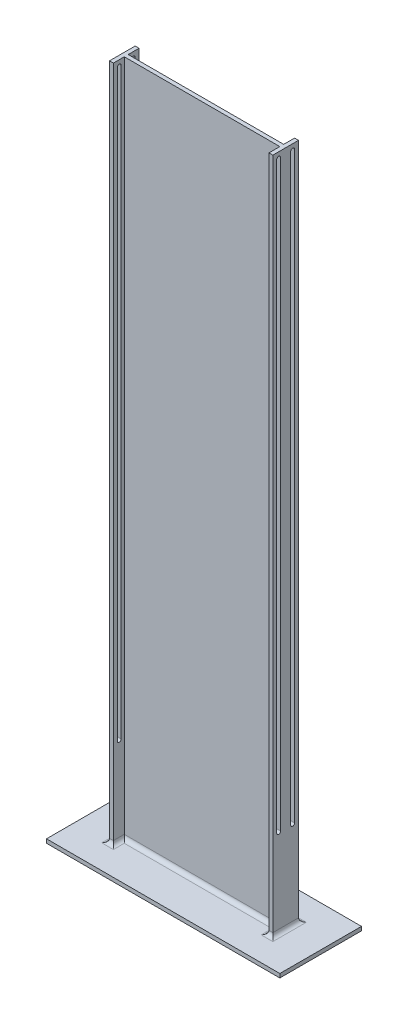
SolidWorks part; units mm, degrees
material "AISI 4340 Steel, annealed"
ref_plane "Front Plane" through (0, 0, 0) normal (0, 0, 1) x (1, 0, 0)
ref_plane "Top Plane" through (0, 0, 0) normal (0, 1, 0) x (1, 0, 0)
ref_plane "Right Plane" through (0, 0, 0) normal (1, 0, 0) x (0, 0, -1)
sketch "Sketch1" plane through (0, 0, 0) normal (1, 0, 0) x (0, 0, -1)
  line L0 (0, 0) -> (-100, 0)
  line L1 (-100, 0) -> (-100, -10)
  line L2 (-100, -10) -> (10, -10)
  line L3 (10, 0) -> (10, 1741.5)
  line L4 (10, 1741.5) -> (0, 1741.5)
  line L5 (0, 1741.5) -> (0, 0)
  line L6 (10, -10) -> (110, -10)
  line L7 (110, -10) -> (110, 0)
  line L8 (110, 0) -> (10, 0)
  point P3 (0, 0)
  dimension "D1" = 1751.5
  dimension "D2" = 10
  dimension "D3" = 10
  dimension "D4" = 100
extrude "Wall extrude" add sketch "Sketch1" along normal mid plane 400
sketch "Sketch2" plane through (200, 0, 0) normal (1, 0, 0) x (0, 0, -1)
  line L0 (5, 1741.5) -> (5, -10) construction
  line L1 (10, 1741.5) -> (0, 1741.5) construction
  line L2 (10, 0) -> (10, 1741.5) construction
  line L3 (-100, -10) -> (110, -10) construction
  line L4 (0, 1741.5) -> (38, 1741.5)
  line L6 (0, -10) -> (38, -10)
  line L7 (38, 1741.5) -> (38, -10)
  line L8 (18, 226.5) -> (18, 1726.5)
  line L9 (28, 1726.5) -> (28, 226.5)
  line L10 (-18, 1726.5) -> (-18, 226.5)
  line L11 (-8, 226.5) -> (-8, 1726.5)
  line L12 (0, 1741.5) -> (-28, 1741.5)
  line L13 (-28, 1741.5) -> (-28, -10)
  line L14 (-28, -10) -> (0, -10)
  line L15 (0, 1741.5) -> (0, 0) construction
  arc A0 (28, 1726.5) -> (18, 1726.5) centre (23, 1726.5) ccw
  arc A1 (18, 226.5) -> (28, 226.5) centre (23, 226.5) ccw
  arc A2 (-8, 226.5) -> (-18, 226.5) centre (-13, 226.5) cw
  arc A3 (-18, 1726.5) -> (-8, 1726.5) centre (-13, 1726.5) cw
  dimension "D1" = 10
  dimension "D5" = 10
  dimension "D2" = 13
  dimension "D3" = 15
  dimension "D4" = 15
  dimension "D6" = 13
  dimension "D7" = 236.5
  dimension "D8" = 5
  dimension "D9" = 28
extrude "Right guide extrude" add sketch "Sketch2" along normal blind 10
mirror "Left guide extrude" about plane through (0, 0, 0) normal (1, 0, 0) of "Right guide extrude"
sketch "Sketch3" plane through (0, -10, 0) normal (0, -1, 0) x (1, 0, 0)
  line L11 (200, 100) -> (-200, 100) construction
  line L12 (-300, 100) -> (300, 100)
  line L15 (-300, 100) -> (-300, -110)
  line L16 (-300, -110) -> (300, -110)
  line L17 (300, 100) -> (300, -110)
  line L18 (200, -110) -> (-200, -110) construction
  line L19 (-200, 100) -> (-200, 28) construction
  line L20 (200, 100) -> (200, 28) construction
  dimension "D2" = 100
  dimension "D1" = 100
extrude "Bottom foot completion" add sketch "Sketch3" against normal blind 10
sketch "Sketch4" plane through (0, 0, -10) normal (0, 0, -1) x (-1, 0, 0)
  line L0 (-200, 0) -> (-200, 1741.5) construction
  line L1 (-200, 136.5) -> (200, 136.5)
  line L2 (-200, 136.5) -> (-200, 126.5)
  line L3 (-200, 126.5) -> (200, 126.5)
  line L4 (200, 136.5) -> (200, 126.5)
  line L5 (200, 0) -> (200, 1741.5) construction
  line L6 (-200, -10) -> (200, -10) construction
  dimension "D1" = 146.5
  dimension "D2" = 10
extrude "Platform stopper" add sketch "Sketch4" along normal up to surface (28 mm away) up to face at (205, 870.75, -38)
fillet "Structural fillets" radius 10 15 edges at (-210, 0, -5) (210, 0, -5) (0, 0, 0) (-200, 126.5, -24) (200, 126.5, -24) (0, 126.5, -10) (200, 0, 14) (-200, 0, 14) (-205, 0, 28) (205, 0, 28) (-205, 0, -38) (-200, 0, -24) (200, 0, -24) (205, 0, -38) (0, 0, -10)
